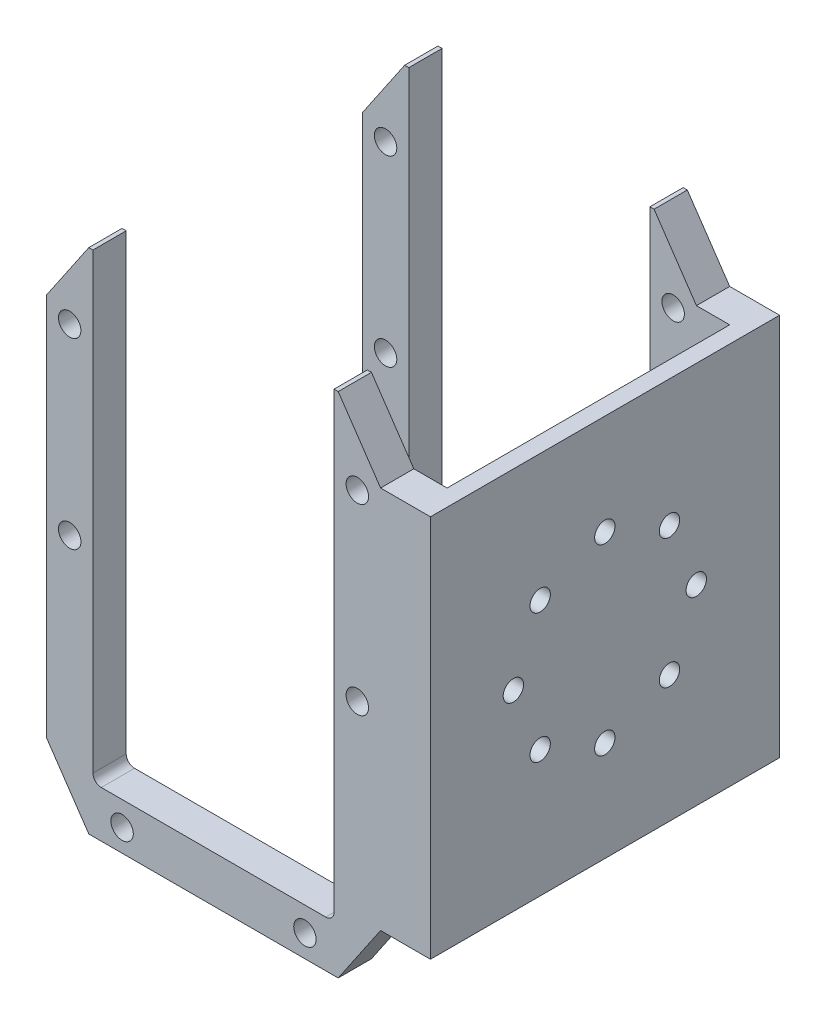
SolidWorks part; units mm, degrees
ref_plane "정면" through (0, 0, 0) normal (0, 0, 1) x (1, 0, 0)
ref_plane "윗면" through (0, 0, 0) normal (0, 1, 0) x (1, 0, 0)
ref_plane "우측면" through (0, 0, 0) normal (1, 0, 0) x (0, 0, -1)
sketch "스케치1" plane through (0, 0, 0) normal (0, 0, 1) x (1, 0, 0)
  line L0 (-14.5, -41.5) -> (-14.5, 11.5)
  line L1 (-14.5, 13) -> (-15, 13)
  line L2 (-15, 13) -> (-20.1, 5.5)
  line L3 (-20.1, 5.5) -> (-20.1, -40.6)
  line L4 (-20.1, -40.6) -> (-15, -48.1)
  line L5 (-15, -48.1) -> (15, -48.1)
  line L6 (15, -48.1) -> (20.1, -40.6)
  line L7 (20.1, -40.6) -> (20.1, 5.5)
  line L8 (20.1, 5.5) -> (15, 13)
  line L9 (15, 13) -> (14.5, 13)
  line L10 (14.5, 11.5) -> (14.5, -41.5)
  line L11 (13.5, -42.5) -> (-13.5, -42.5)
  line L12 (0, 0) -> (0, 13) construction
  line L13 (0, 13) -> (0, -42.5) construction
  line L14 (-14.5, 11.5) -> (-14.5, 13)
  line L15 (14.5, 11.5) -> (14.5, 13)
  arc A0 (-13.5, -42.5) -> (-14.5, -41.5) centre (-13.5, -41.5) cw
  arc A3 (14.5, -41.5) -> (13.5, -42.5) centre (13.5, -41.5) cw
  circle A4 centre (-17.3, -18.13) radius 1.35
  circle A5 centre (-17.3, 3.87) radius 1.35
  circle A6 centre (-11, -45.4056) radius 1.35
  circle A7 centre (11, -45.4056) radius 1.35
  circle A8 centre (17.3, -18.13) radius 1.35
  circle A9 centre (17.3, 3.87) radius 1.35
  dimension "D1" = 2.7
  dimension "D3" = 22
  dimension "D4" = 6.3
  dimension "D8" = 15
  dimension "D9" = 1
  dimension "D2" = 17.3
  dimension "D5" = 14.5
  dimension "D6" = 20.1
  dimension "D7" = 7.5
  dimension "D10" = 3.87
  dimension "D11" = 5.5
  dimension "D12" = 11.5
  dimension "D13" = 40.6
  dimension "D15" = 42.5
  dimension "D16" = 45.4056
extrude "보스-돌출2" add sketch "스케치1" along normal blind 42 contours L3 L4 L5 L6 L7 L8 L9 L15 L10 A3 L11 A0 L0 L14 L1 L2
sketch "스케치2" plane through (0, 0, 0) normal (0, 0, -1) x (-1, 0, 0)
  circle A1 centre (-11, -45.4056) radius 1.35
  circle A2 centre (-11, -45.4056) radius 1.35
  circle A3 centre (11, -45.4056) radius 1.35
  circle A4 centre (11, -45.4056) radius 1.35
  circle A5 centre (17.3, 3.87) radius 1.35
  circle A6 centre (17.3, 3.87) radius 1.35
  circle A7 centre (17.3, -18.13) radius 1.35
  circle A8 centre (17.3, -18.13) radius 1.35
  circle A9 centre (-17.3, 3.87) radius 1.35
  circle A10 centre (-17.3, 3.87) radius 1.35
  circle A11 centre (-17.3, -18.13) radius 1.35
  circle A12 centre (-17.3, -18.13) radius 1.35
  dimension "D1" = 0
  dimension "D2" = 0
  dimension "D3" = 0
  dimension "D4" = 0
  dimension "D5" = 0
  dimension "D6" = 0
extrude "컷-돌출1" cut sketch "스케치2" against normal blind 45
sketch "스케치3" plane through (20.1, 0, 0) normal (1, 0, 0) x (0, 0, -1)
  line L0 (-38, 5.5) -> (-38, -40.6)
  line L1 (-42, 5.5) -> (0, 5.5) construction
  line L2 (-42, -40.6) -> (0, -40.6) construction
  line L3 (-38, 5.5) -> (-38, 13)
  line L4 (-4, -40.6) -> (-4, 5.5)
  line L5 (-42, 13) -> (0, 13) construction
  line L6 (-42, -40.6) -> (-42, 5.5) construction
  line L7 (0, -40.6) -> (0, 5.5) construction
  line L8 (-38, 13) -> (-4, 13)
  line L9 (-4, 13) -> (-4, 5.5)
  line L10 (-4, -40.6) -> (-4, -48.1)
  line L11 (-42, -48.1) -> (0, -48.1) construction
  line L12 (-4, -48.1) -> (-38, -48.1)
  line L13 (-38, -48.1) -> (-38, -40.6)
  dimension "D1" = 4
  dimension "D2" = 4
  dimension "D3" = 34
extrude "컷-돌출2" cut sketch "스케치3" against normal blind 45
sketch "스케치4" plane through (20.1, 0, 0) normal (1, 0, 0) x (0, 0, -1)
  line L0 (-42, 5.5) -> (-38, 5.5)
  line L1 (-38, 5.5) -> (-38, -40.6)
  line L2 (-38, 5.5) -> (-38, -40.6) construction
  line L3 (-38, -40.6) -> (-42, -40.6)
  line L4 (-42, -40.6) -> (-42, 5.5)
  line L5 (-4, 5.5) -> (0, 5.5)
  line L6 (0, 5.5) -> (0, -40.6)
  line L7 (0, -40.6) -> (-4, -40.6)
  line L8 (-4, -40.6) -> (-4, 5.5)
extrude "보스-돌출3" add sketch "스케치4" along normal blind 4
sketch "스케치5" plane through (0, 0, 42) normal (0, 0, 1) x (1, 0, 0)
  line L0 (24.1, 5.5) -> (26.1, 5.5)
  line L1 (26.1, 5.5) -> (26.1, -40.6)
  line L2 (26.1, -40.6) -> (24.1, -40.6)
  line L3 (24.1, -40.6) -> (24.1, 5.5)
  dimension "D1" = 2
extrude "보스-돌출4" add sketch "스케치5" against normal blind 42
sketch "스케치6" plane through (26.1, 0, 0) normal (1, 0, 0) x (0, 0, -1)
  line L0 (-21, 5.5) -> (-21, -40.6) construction
  line L1 (0, 5.5) -> (-42, 5.5) construction
  line L2 (0, -40.6) -> (-42, -40.6) construction
  line L3 (0, -17.55) -> (-42, -17.55) construction
  line L4 (0, -40.6) -> (0, 5.5) construction
  line L5 (-42, -40.6) -> (-42, 5.5) construction
  circle A0 centre (-28.8011, -9.7824) radius 1.225
  circle A1 centre (-21.0229, -6.5606) radius 1.225
  circle A2 centre (-13.2447, -9.7824) radius 1.225
  circle A3 centre (-10.0229, -17.5606) radius 1.225
  circle A4 centre (-13.2447, -25.3387) radius 1.225
  circle A5 centre (-21.0229, -28.5606) radius 1.225
  circle A6 centre (-28.8011, -25.3387) radius 1.225
  circle A7 centre (-32.0229, -17.5606) radius 1.225
  dimension "D1" = 2.45
  dimension "D2" = 9.9771
  dimension "D3" = 13.1989
  dimension "D4" = 20.9771
  dimension "D5" = 28.7553
  dimension "D6" = 31.9771
  dimension "D7" = 12.0394
  dimension "D8" = 15.2613
  dimension "D9" = 23.0394
  dimension "D10" = 30.8176
  dimension "D11" = 34.0394
extrude "컷-돌출3" cut sketch "스케치6" against normal blind 10
